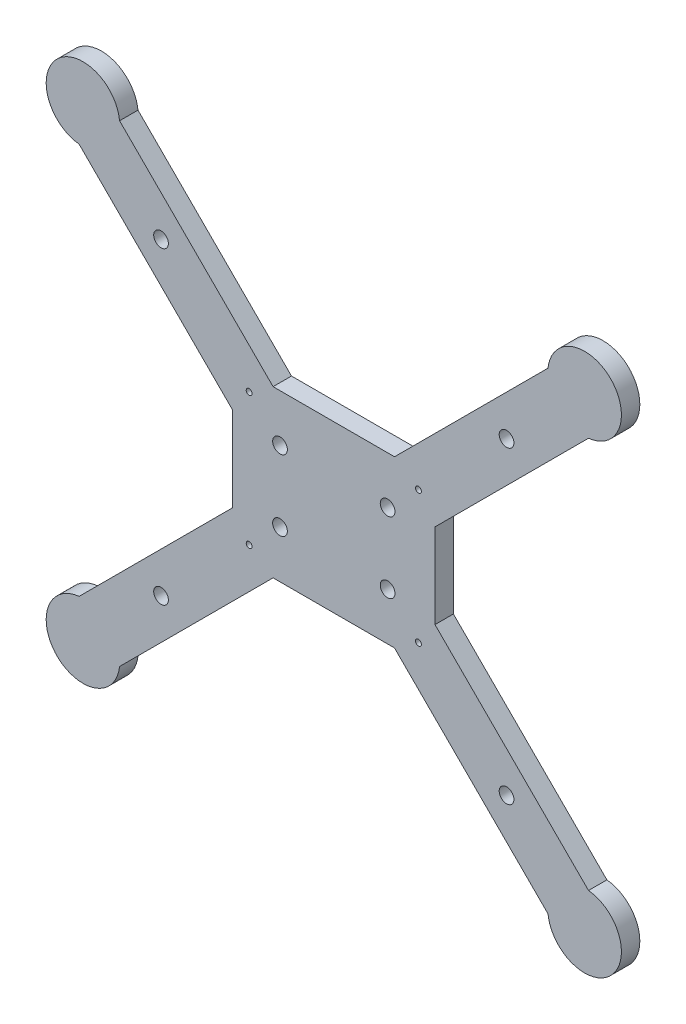
SolidWorks part; units mm, degrees
ref_plane "Plan de face" through (0, 0, 0) normal (0, 0, 1) x (1, 0, 0)
ref_plane "Plan de dessus" through (0, 0, 0) normal (0, 1, 0) x (1, 0, 0)
ref_plane "Plan de droite" through (0, 0, 0) normal (1, 0, 0) x (0, 0, -1)
sketch "Esquisse1" plane through (0, 0, 0) normal (0, 0, 1) x (1, 0, 0)
  line L0 (-55, 23) -> (-147.3173, 115.3173)
  line L1 (55, -45) -> (-55, -45)
  line L2 (55, -45) -> (55, 45)
  line L3 (55, 45) -> (-55, 45)
  line L4 (-55, -45) -> (-55, 45)
  line L5 (-147.3173, 115.3173) -> (-125.3173, 137.3173)
  line L6 (-125.3173, 137.3173) -> (-33, 45)
  line L7 (33, 45) -> (125.3173, 137.3173)
  line L8 (125.3173, 137.3173) -> (147.3173, 115.3173)
  line L9 (147.3173, 115.3173) -> (55, 23)
  line L10 (-55, -23) -> (-147.3173, -115.3173)
  line L11 (-147.3173, -115.3173) -> (-125.3173, -137.3173)
  line L12 (-125.3173, -137.3173) -> (-33, -45)
  line L13 (33, -45) -> (125.3173, -137.3173)
  line L14 (125.3173, -137.3173) -> (147.3173, -115.3173)
  line L15 (147.3173, -115.3173) -> (55, -23)
  line L16 (-55, 45) -> (55, -45) construction
  circle A0 centre (-136.3173, 126.3173) radius 20
  circle A1 centre (136.3173, 126.3173) radius 20
  circle A2 centre (136.3173, -126.3173) radius 20
  circle A3 centre (-136.3173, -126.3173) radius 20
  dimension "D16" = 40
  dimension "D17" = 40
  dimension "D18" = 40
  dimension "D19" = 40
  dimension "D1" = 90
  dimension "D3" = 22
  dimension "D4" = 22
  dimension "D2" = 22
  dimension "D5" = 22
  dimension "D6" = 22
  dimension "D7" = 22
  dimension "D8" = 22
  dimension "D9" = 22
  dimension "D10" = 45
  dimension "D11" = 45
  dimension "D12" = 115
  dimension "D13" = 115
  dimension "D14" = 115
  dimension "D15" = 115
  dimension "D20" = 110
extrude "Boss.-Extru.1" add sketch "Esquisse1" along normal blind 10 contours L6 A0 L0 L5 | L0 A0 L6 L5 | A0 L0 L4 L3 L6 | A1 L7 L3 L2 L9 | L9 A1 L7 L8 | L7 A1 L9 L8 | L4 L1 L2 L3 | L13 A2 L15 L14 | L15 A2 L13 L14 | A2 L15 L2 L1 L13 | L10 A3 L12 L11 | L12 A3 L10 L11 | A3 L12 L1 L4 L10
sketch "Esquisse3" plane through (0, 0, 0) normal (0, 0, -1) x (-1, 0, 0)
  line L0 (-150.4594, 140.4594) -> (-44, 34) construction
  line L1 (-55, 23) -> (-33, 45) construction
  line L2 (-33, -45) -> (33, -45) construction
  line L3 (-33, 45) -> (33, 45) construction
  line L4 (-55, 0) -> (55, 0) construction
  line L5 (-55, -23) -> (-55, 23) construction
  line L6 (55, -23) -> (55, 23) construction
  line L7 (0, -45) -> (0, 45) construction
  line L10 (-46, 36) -> (46, 36) construction
  line L11 (-46, 36) -> (-46, -36) construction
  arc A0 (-116.4291, 128.4291) -> (-138.4291, 106.4291) centre (-136.3173, 126.3173) ccw construction
  circle A3 centre (93.8909, 83.8909) radius 4
  circle A4 centre (-93.8909, 83.8909) radius 4
  circle A5 centre (-29.2384, 19.2384) radius 4
  circle A16 centre (-46, 36) radius 1.6
  circle A17 centre (46, 36) radius 1.6
  circle A18 centre (46, -36) radius 1.6
  circle A19 centre (-46, -36) radius 1.6
  circle A21 centre (29.2384, 19.2384) radius 4
  circle A22 centre (-93.8909, -83.8909) radius 4
  circle A23 centre (-29.2384, -19.2384) radius 4
  circle A24 centre (29.2384, -19.2384) radius 4
  circle A25 centre (93.8909, -83.8909) radius 4
  dimension "D1" = 8
  dimension "D2" = 8
  dimension "D7" = 3.2
  dimension "D3" = 80
  dimension "D4" = 35
  dimension "D8" = 36
  dimension "D10" = 2
  dimension "D11" = 2
  dimension "D9" = 46
  dimension "D12" = 92
  dimension "D13" = 72
extrude "Enlèv. mat.-Extru.2" cut sketch "Esquisse3" against normal through all
equation "\"L\"= 115"
equation "\"e\"= 22"
equation "\"D15@Esquisse1\"=\"L\""
equation "\"D14@Esquisse1\"=\"L\""
equation "\"D13@Esquisse1\"=\"L\""
equation "\"D12@Esquisse1\"=\"L\""
equation "\"D8@Esquisse1\"=\"e\""
equation "\"D9@Esquisse1\"=\"e\""
equation "\"D3@Esquisse1\"=\"e\""
equation "\"D4@Esquisse1\"=\"e\""
equation "\"D2@Esquisse1\"=\"e\""
equation "\"D5@Esquisse1\"=\"e\""
equation "\"D6@Esquisse1\"=\"e\""
equation "\"D7@Esquisse1\"=\"e\""
equation "\"d\"= 40"
equation "\"D17@Esquisse1\"=\"d\""
equation "\"D16@Esquisse1\"=\"d\""
equation "\"D19@Esquisse1\"=\"d\""
equation "\"D18@Esquisse1\"=\"d\""
